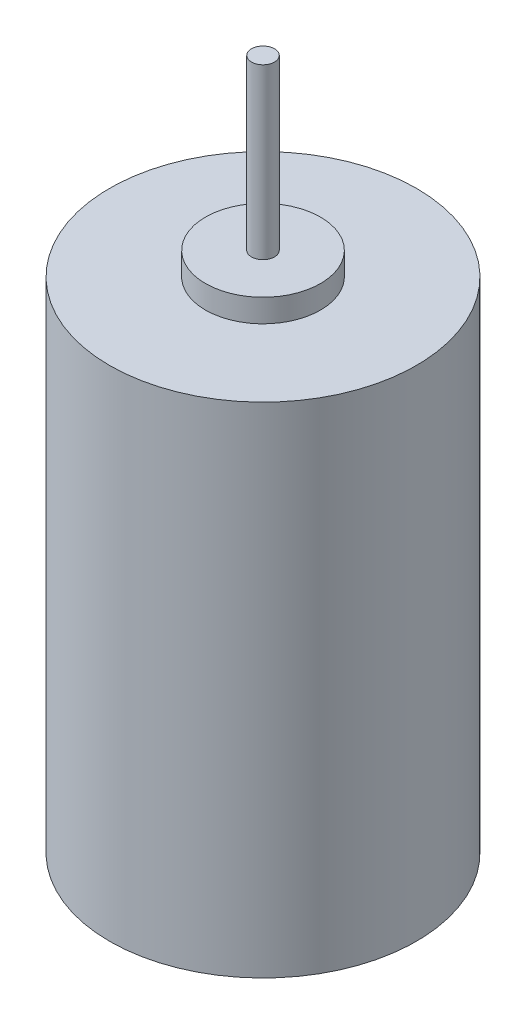
SolidWorks part; units mm, degrees
ref_plane "Front Plane" through (0, 0, 0) normal (0, 0, 1) x (1, 0, 0)
ref_plane "Top Plane" through (0, 0, 0) normal (0, 1, 0) x (1, 0, 0)
ref_plane "Right Plane" through (0, 0, 0) normal (1, 0, 0) x (0, 0, -1)
sketch "Sketch1" plane through (0, 0, 0) normal (0, 1, 0) x (1, 0, 0)
  circle A0 centre (0, 0) radius 20
  dimension "D1" = 40
extrude "Boss-Extrude1" add sketch "Sketch1" along normal blind 65
sketch "Sketch2" plane through (0, 65, 0) normal (0, 1, 0) x (1, 0, 0)
  circle A0 centre (0, 0) radius 7.5
  dimension "D1" = 15
extrude "Boss-Extrude2" add sketch "Sketch2" along normal blind 3 and the other way blind 68
sketch "Sketch3" plane through (0, 0, 0) normal (0, 1, 0) x (1, 0, 0)
  circle A0 centre (0, 0) radius 1.5
  dimension "D1" = 3
extrude "Boss-Extrude3" add sketch "Sketch3" along normal blind 90 and the other way blind 10
sketch "Sketch4" plane through (0, 65, 0) normal (0, 1, 0) x (1, 0, 0)
  line L0 (0, 1.5) -> (-1.5, 0)
  circle A0 centre (0, 0) radius 1.5 construction
  circle A1 centre (0, 0) radius 1.5 construction
